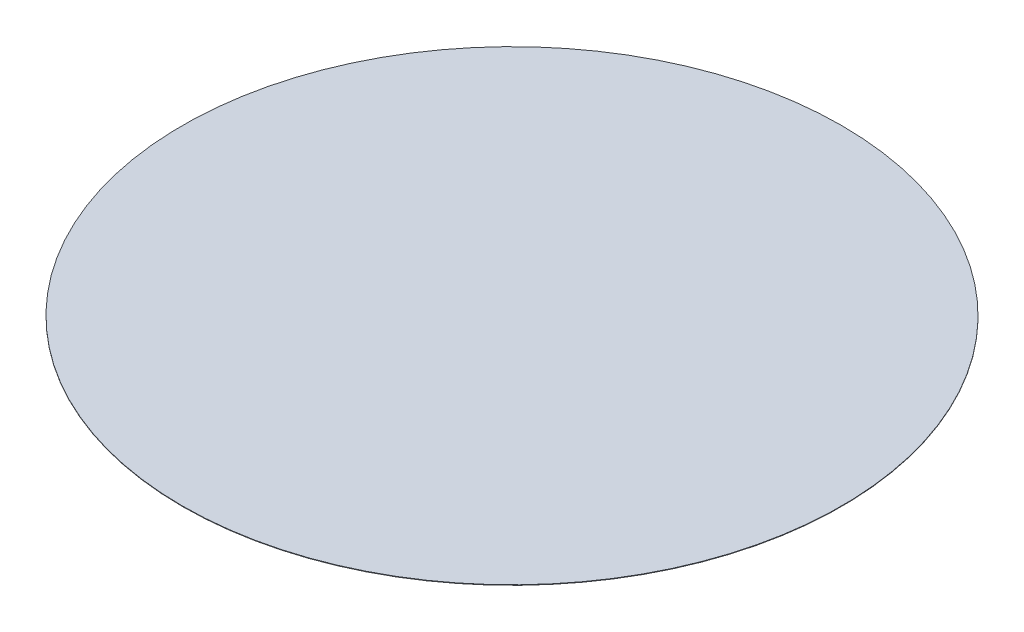
SolidWorks part; units mm, degrees
ref_plane "Front Plane" through (0, 0, 0) normal (0, 0, 1) x (1, 0, 0)
ref_plane "Top Plane" through (0, 0, 0) normal (0, 1, 0) x (1, 0, 0)
ref_plane "Right Plane" through (0, 0, 0) normal (1, 0, 0) x (0, 0, -1)
sketch "Sketch1" plane through (0, 0, 0) normal (0, 1, 0) x (1, 0, 0)
  circle A0 centre (0, 0) radius 2750
extrude "Boss-Extrude1" add sketch "Sketch1" against normal blind 4
